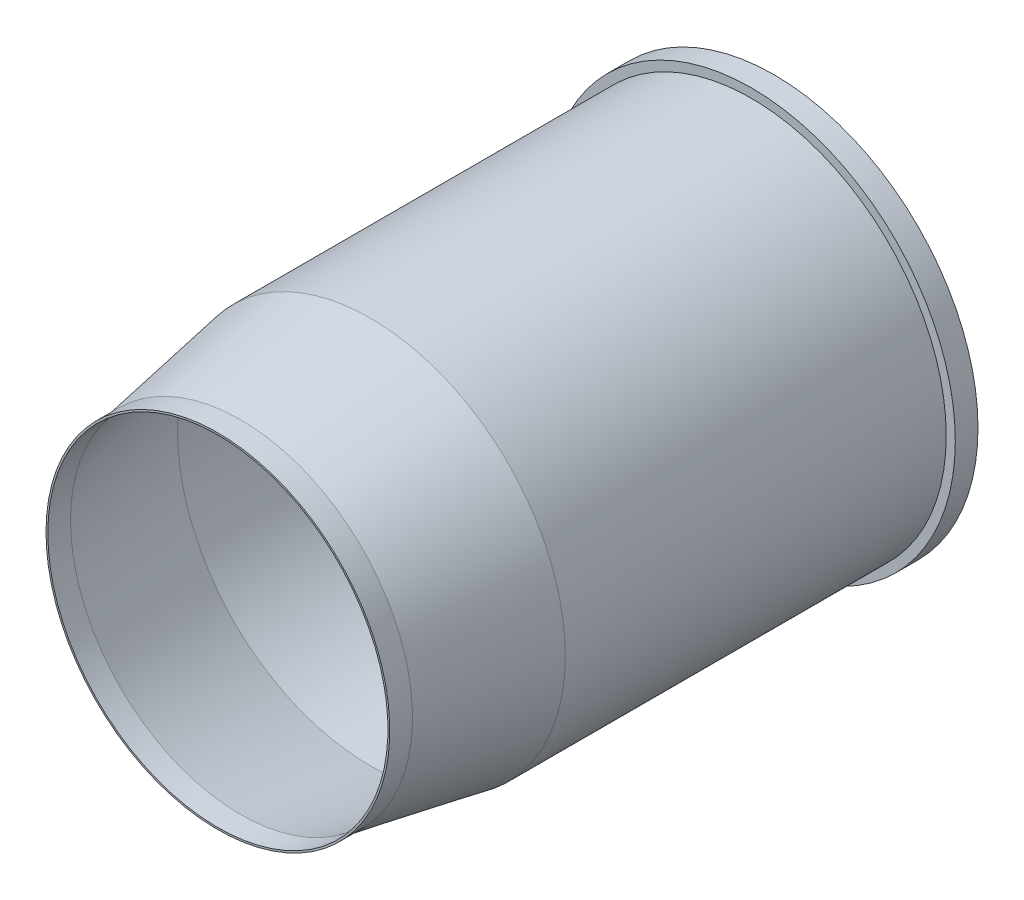
SolidWorks part; units mm, degrees
ref_plane "Front Plane" through (0, 0, 0) normal (0, 0, 1) x (1, 0, 0)
ref_plane "Top Plane" through (0, 0, 0) normal (0, 1, 0) x (1, 0, 0)
ref_plane "Right Plane" through (0, 0, 0) normal (1, 0, 0) x (0, 0, -1)
sketch "Sketch1" plane through (0, 0, 0) normal (1, 0, 0) x (0, 0, -1)
  line L0 (0, 0) -> (-61.2273, 0) construction
  line L1 (0, 42.5) -> (-88.877, 42.5)
  line L2 (-88.877, 42.5) -> (-117.5, 37.453)
  line L4 (-117.5, 37.853) -> (-88.877, 42.9)
  line L5 (-88.877, 42.9) -> (-5, 42.9)
  line L6 (-5, 42.9) -> (-5, 44.9)
  line L7 (-5, 44.9) -> (0, 44.9)
  line L8 (0, 44.9) -> (0, 42.5)
  line L9 (-88.877, 42.5) -> (-88.877, 33.5588) construction
  line L10 (-117.5, 37.853) -> (-122.5, 37.853)
  line L11 (-122.5, 37.853) -> (-122.5, 37.453)
  line L12 (-122.5, 37.453) -> (-117.5, 37.453)
  dimension "D1" = 89.8
  dimension "D2" = 0.4
  dimension "D3" = 2.4
  dimension "D4" = 0.4
  dimension "D5" = 80
  dimension "D6" = 5
  dimension "D7" = 75.706
  dimension "D8" = 122.5
  dimension "D9" = 5
revolve "Revolve1" add sketch "Sketch1" angle 360 about L0
